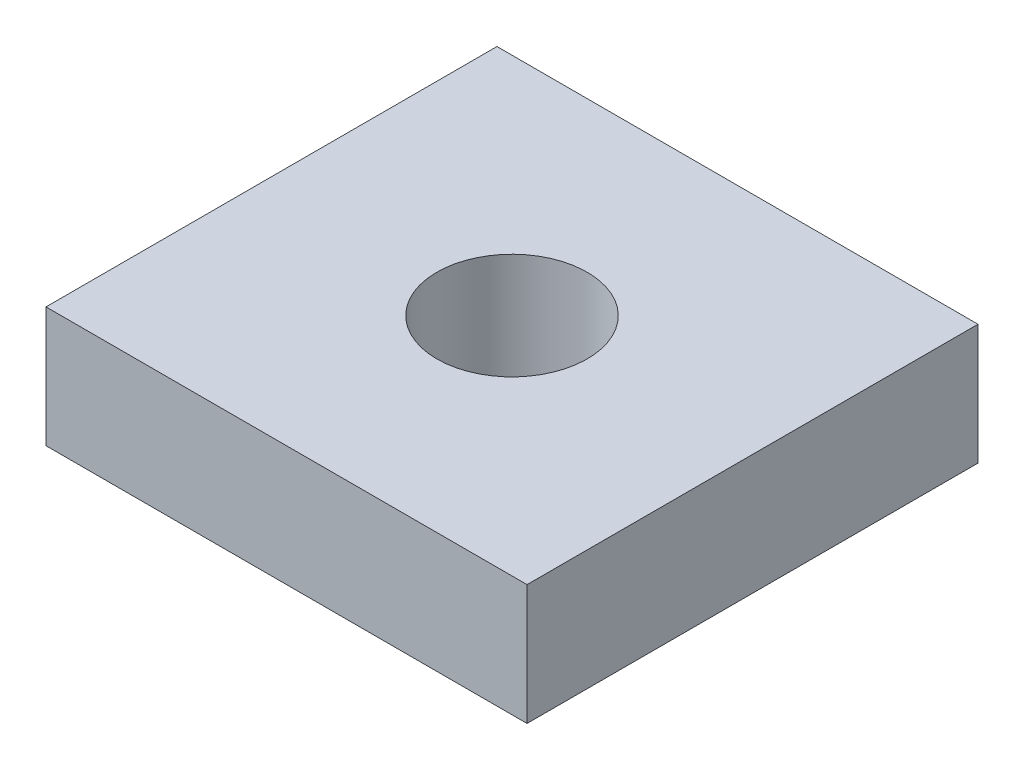
SolidWorks part; units mm, degrees
ref_plane "Ön Düzlem" through (0, 0, 0) normal (0, 0, 1) x (1, 0, 0)
ref_plane "Üst Düzlem" through (0, 0, 0) normal (0, 1, 0) x (1, 0, 0)
ref_plane "Sağ Düzlem" through (0, 0, 0) normal (1, 0, 0) x (0, 0, -1)
sketch "Çizim1" plane through (0, 0, 0) normal (0, 1, 0) x (1, 0, 0)
  line L0 (-8, 7.5) -> (-8, -7.5)
  line L1 (-8, -7.5) -> (8, -7.5)
  line L3 (-8, 7.5) -> (8, 7.5)
  line L4 (8, -7.5) -> (8, 7.5)
  line L5 (-8, -7.5) -> (8, 7.5) construction
  line L6 (-8, 7.5) -> (8, -7.5) construction
  circle A0 centre (0, 0) radius 2.5
  dimension "D1" = 5
  dimension "D2" = 16
  dimension "D3" = 16
  dimension "D4" = 15
extrude "Yükseklik-Ekstrüzyon1" add sketch "Çizim1" along normal blind 4
